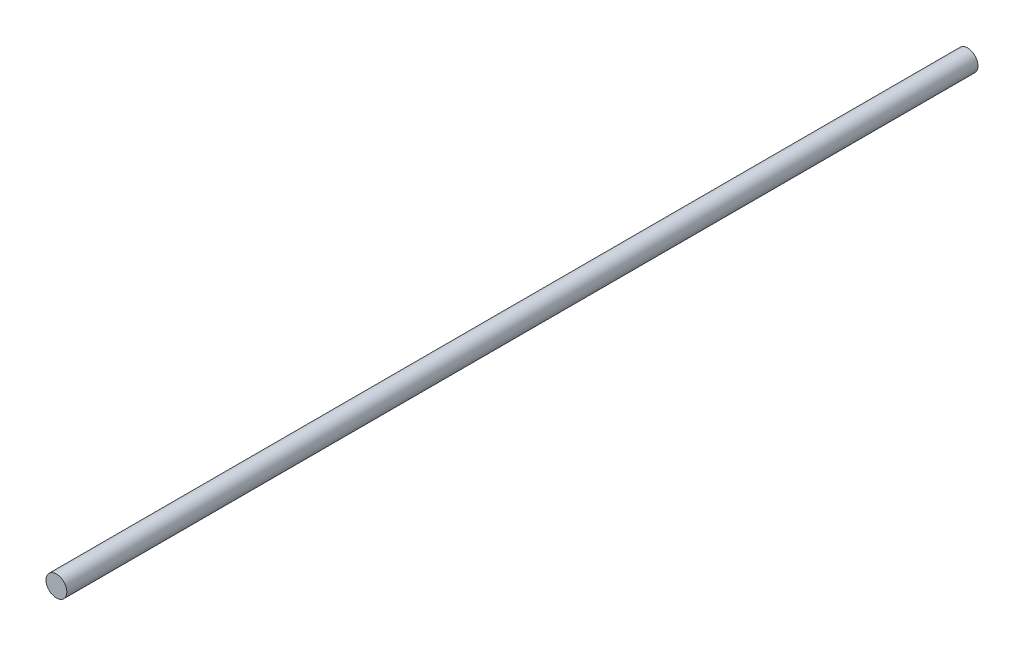
SolidWorks part; units mm, degrees
ref_plane "前视基准面" through (0, 0, 0) normal (0, 0, 1) x (1, 0, 0)
ref_plane "上视基准面" through (0, 0, 0) normal (0, 1, 0) x (1, 0, 0)
ref_plane "右视基准面" through (0, 0, 0) normal (1, 0, 0) x (0, 0, -1)
sketch "草图1" plane through (0, 0, 0) normal (0, 0, 1) x (1, 0, 0)
  circle A0 centre (0, 0) radius 8
  dimension "D1" = 16
extrude "凸台-拉伸1" add sketch "草图1" along normal blind 700
